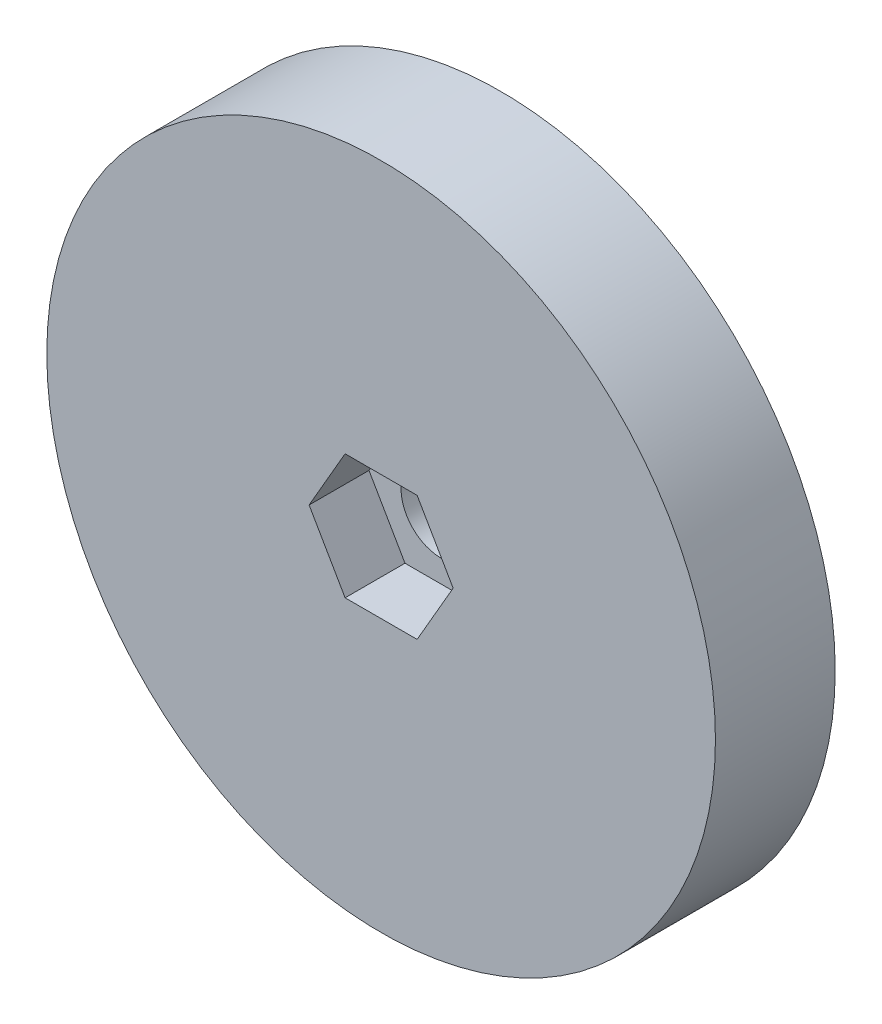
SolidWorks part; units mm, degrees
ref_plane "Front Plane" through (0, 0, 0) normal (0, 0, 1) x (1, 0, 0)
ref_plane "Top Plane" through (0, 0, 0) normal (0, 1, 0) x (1, 0, 0)
ref_plane "Right Plane" through (0, 0, 0) normal (1, 0, 0) x (0, 0, -1)
sketch "Sketch1" plane through (0, 0, 0) normal (0, 0, 1) x (1, 0, 0)
  circle A0 centre (0, 0) radius 4
  circle A1 centre (0, 0) radius 33.5
  dimension "D1" = 67
  dimension "D2" = 8
extrude "Boss-Extrude1" add sketch "Sketch1" along normal blind 12
sketch "Sketch2" plane through (0, 0, 12) normal (0, 0, 1) x (1, 0, 0)
  line L1 (7.2169, 0) -> (3.6084, 6.25)
  line L2 (3.6084, 6.25) -> (-3.6084, 6.25)
  line L3 (-3.6084, 6.25) -> (-7.2169, 0)
  line L4 (-7.2169, 0) -> (-3.6084, -6.25)
  line L5 (-3.6084, -6.25) -> (3.6084, -6.25)
  line L6 (3.6084, -6.25) -> (7.2169, 0)
  circle A0 centre (0, 0) radius 6.25 construction
  dimension "D1" = 12.5
extrude "Cut-Extrude1" cut sketch "Sketch2" against normal blind 6
